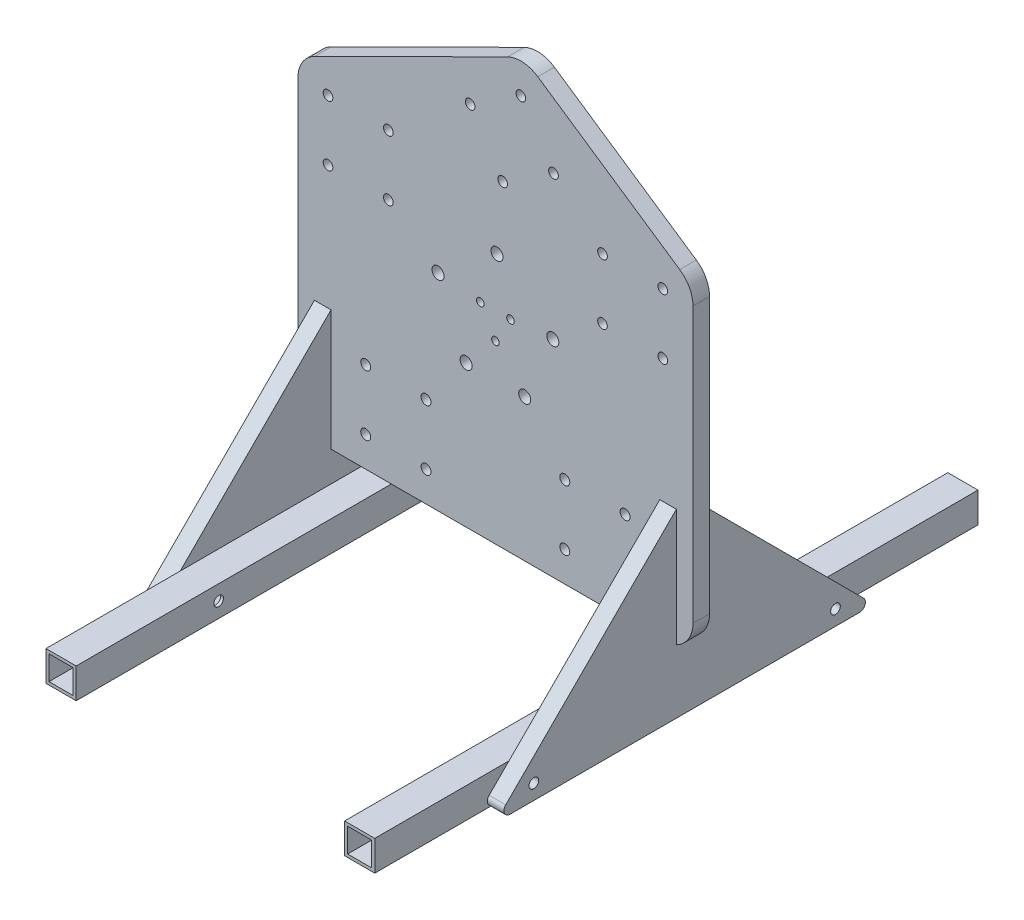
SolidWorks part; units mm, degrees
material "ﾊﾞﾙｻ"
ref_plane "正面" through (0, 0, 0) normal (0, 0, 1) x (1, 0, 0)
ref_plane "平面" through (0, 0, 0) normal (0, 1, 0) x (1, 0, 0)
ref_plane "右側面" through (0, 0, 0) normal (1, 0, 0) x (0, 0, -1)
sketch "ｽｹｯﾁ2" plane through (0, 0, 0) normal (0, 0, 1) x (1, 0, 0)
  line L0 (0, 0) -> (0, -52) construction
  line L5 (-23, -22) -> (-43, -22) construction
  line L6 (-23, -22) -> (-23, -42) construction
  line L7 (-23, -42) -> (-43, -42) construction
  line L8 (-43, -22) -> (-43, -42) construction
  line L9 (43, -22) -> (43, -42) construction
  line L10 (23, -42) -> (43, -42) construction
  line L11 (23, -22) -> (23, -42) construction
  line L12 (23, -22) -> (43, -22) construction
  line L13 (-23, -22) -> (-6, 0) construction
  line L14 (-35.5, 29.0934) -> (-13.5, 12.0934) construction
  line L15 (35.5, 49.0934) -> (35.5, 29.0934) construction
  line L16 (-55.5, 49.0934) -> (-35.5, 49.0934) construction
  line L17 (-55.5, 49.0934) -> (-55.5, 29.0934) construction
  line L18 (-55.5, 29.0934) -> (-35.5, 29.0934) construction
  line L19 (-35.5, 49.0934) -> (-35.5, 29.0934) construction
  line L20 (55.5, 29.0934) -> (35.5, 29.0934) construction
  line L21 (55.5, 49.0934) -> (55.5, 29.0934) construction
  line L22 (55.5, 49.0934) -> (35.5, 49.0934) construction
  line L23 (35.5, 29.0934) -> (13.5, 12.0934) construction
  line L24 (2.4232, 53.2905) -> (0, 25.5934) construction
  line L25 (8.4514, 80.9249) -> (19.2545, 64.0936) construction
  line L26 (8.4514, 80.9249) -> (-8.3799, 70.1218) construction
  line L27 (-8.3799, 70.1218) -> (2.4232, 53.2905) construction
  line L28 (19.2545, 64.0936) -> (2.4232, 53.2905) construction
  line L29 (23, -22) -> (6, 0) construction
  line L30 (-65.5, 49.0934) -> (-65.5, -42)
  line L31 (-55.5, -52) -> (55.5, -52)
  line L32 (65.5, -42) -> (65.5, 49.0934)
  line L33 (61.1036, 57.3759) -> (14.055, 89.2074)
  line L34 (3.9954, 89.8772) -> (-59.956, 58.0457)
  line L35 (0, 12.0934) -> (0, 6.3199) construction
  circle A0 centre (-43, -42) radius 1.65
  circle A1 centre (-43, -22) radius 1.65
  circle A2 centre (-23, -22) radius 1.65
  circle A3 centre (-23, -42) radius 1.65
  circle A8 centre (23, -42) radius 1.65
  circle A9 centre (23, -22) radius 1.65
  circle A10 centre (43, -22) radius 1.65
  circle A11 centre (43, -42) radius 1.65
  circle A12 centre (-55.5, 49.0934) radius 1.6
  circle A13 centre (-55.5, 29.0934) radius 1.6
  circle A14 centre (-35.5, 29.0934) radius 1.6
  circle A15 centre (-35.5, 49.0934) radius 1.6
  circle A16 centre (35.5, 49.0934) radius 1.6
  circle A17 centre (35.5, 29.0934) radius 1.6
  circle A18 centre (55.5, 29.0934) radius 1.6
  circle A19 centre (55.5, 49.0934) radius 1.6
  circle A20 centre (8.4514, 80.9249) radius 1.6
  circle A21 centre (-8.3799, 70.1218) radius 1.6
  circle A22 centre (2.4232, 53.2905) radius 1.6
  circle A23 centre (19.2545, 64.0936) radius 1.6
  circle A24 centre (0, 12.0934) radius 13.5 construction
  arc A25 (-65.5, -42) -> (-55.5, -52) centre (-55.5, -42) ccw
  arc A26 (55.5, -52) -> (65.5, -42) centre (55.5, -42) ccw
  arc A27 (65.5, 49.0934) -> (61.1036, 57.3759) centre (55.5, 49.0934) ccw
  arc A28 (14.055, 89.2074) -> (3.9954, 89.8772) centre (8.4514, 80.9249) ccw
  arc A29 (-65.5, 49.0934) -> (-59.956, 58.0457) centre (-55.5, 49.0934) cw
  circle A30 centre (0, 12.0934) radius 19.5 construction
  circle A31 centre (-19.0266, 16.364) radius 2
  circle A32 centre (0.5243, 31.5863) radius 2
  circle A33 centre (19.0266, 16.364) radius 2
  circle A34 centre (9.7185, -4.8122) radius 2
  circle A35 centre (-9.7185, -4.8122) radius 2
  circle A36 centre (0, 6.3199) radius 1.25
  circle A37 centre (-5, 14.9801) radius 1.25
  circle A38 centre (5, 14.9801) radius 1.25
  point P78 (-6, 16.6629)
  point P79 (0, 12.0934)
  point P83 (0, 12.0934)
  point P84 (0, 0)
  point P85 (0, 0)
  point P86 (-48.6934, -43.9577)
  point P87 (0, 0)
  dimension "D5" = 3.3
  dimension "D9" = 3.2
  dimension "D13" = 27
  dimension "D14" = 10
  dimension "D16" = 6
  dimension "D17" = 4
  dimension "D18" = 2.5
  dimension "D1" = 20
  dimension "D2" = 17
  dimension "D3" = 22
  dimension "D4" = 20
  dimension "D6" = 6
  dimension "D7" = 20
  dimension "D8" = 20
  dimension "D10" = 17
  dimension "D11" = 22
  dimension "D15" = 175
  dimension "D20" = 10
  dimension "D12" = 2
  dimension "D19" = 3
extrude "ﾎﾞｽ - 押し出し1" add sketch "ｽｹｯﾁ2" along normal blind 5.5
sketch "ｽｹｯﾁ4" plane through (0, 0, 0) normal (0, 0, -1) x (-1, 0, 0)
  circle A0 centre (-0.5243, 31.5863) radius 1.7
  circle A1 centre (-19.0266, 16.364) radius 1.7
  circle A2 centre (19.0266, 16.364) radius 1.7
  circle A3 centre (9.7185, -4.8122) radius 1.7
  circle A4 centre (-9.7185, -4.8122) radius 1.7
  circle A6 centre (0, 12.0934) radius 19.5 construction
  circle A7 centre (0, 12.0934) radius 24.5
  circle A8 centre (0, 6.3199) radius 1.6
  circle A9 centre (0, 6.3199) radius 1.25 construction
  circle A10 centre (-5, 14.9801) radius 1.6
  circle A11 centre (5, 14.9801) radius 1.6
  dimension "D1" = 3.4
  dimension "D2" = 5
  dimension "D3" = 3.2
extrude "ﾎﾞｽ - 押し出し2" add sketch "ｽｹｯﾁ4" along normal blind 10 separate body
sketch "ｽｹｯﾁ6" plane through (0, 0, 5.5) normal (0, 0, 1) x (1, 0, 0)
  line L0 (0, 0) -> (0, -52) construction
  line L1 (-55.5, -52) -> (55.5, -52) construction
  line L2 (65.5, -42) -> (65.5, 49.0934) construction
  line L3 (54.5, -32) -> (60, -32)
  line L4 (54.5, -32) -> (54.5, -52)
  line L5 (54.5, -52) -> (60, -52)
  line L6 (60, -32) -> (60, -52)
  line L7 (-54.5, -52) -> (-60, -52)
  line L8 (-60, -32) -> (-60, -52)
  line L9 (-54.5, -32) -> (-60, -32)
  line L10 (-54.5, -32) -> (-54.5, -52)
  point P11 (55.5, -58.7443)
  dimension "D1" = 5.5
  dimension "D2" = 5.5
  dimension "D3" = 20
extrude "ｶｯﾄ - 押し出し1" cut sketch "ｽｹｯﾁ6" against normal through all
sketch "ｽｹｯﾁ7" plane through (60, 0, 0) normal (-1, 0, 0) x (0, 0, 1)
  line L0 (0, -32) -> (5.5, -32)
  line L1 (0, -32) -> (5.5, -32) construction
  line L2 (5.5, -32) -> (5.5, -12)
  line L3 (5.5, -12) -> (65.5, -72)
  line L4 (65.5, -72) -> (-60, -72)
  line L5 (2.75, -72) -> (2.75, -32) construction
  line L6 (5.5, -42) -> (5.5, 49.0934) construction
  line L7 (0, -52) -> (5.5, -52) construction
  line L8 (0, -32) -> (0, -12)
  line L9 (0, -12) -> (-60, -72)
  point P7 (11.6716, -14.7187)
  dimension "D1" = 20
  dimension "D2" = 20
  dimension "D3" = 45
extrude "ﾎﾞｽ - 押し出し3" add sketch "ｽｹｯﾁ7" along normal blind 5.5 separate body
fillet "ﾌｨﾚｯﾄ1" radius 2 2 edges at (57.25, -72, -60) (57.25, -72, 65.5)
mirror "ﾐﾗｰ1" about plane through (0, 0, 0) normal (1, 0, 0) of bodies 104
sketch "ｽｹｯﾁ8" plane through (0, 0, 0) normal (0, 0, 1) x (1, 0, 0)
  line L0 (-53.5, -71) -> (-45.5, -71)
  line L1 (-54.5, -72) -> (-44.5, -72)
  line L2 (-54.5, -72) -> (-54.5, -62)
  line L3 (-54.5, -62) -> (-44.5, -62)
  line L4 (-44.5, -72) -> (-44.5, -62)
  line L5 (-45.5, -71) -> (-45.5, -63)
  line L6 (-53.5, -63) -> (-45.5, -63)
  line L7 (-53.5, -71) -> (-53.5, -63)
  dimension "D1" = 1
  dimension "D2" = 10
  dimension "D3" = 10
extrude "ﾎﾞｽ - 押し出し4" add sketch "ｽｹｯﾁ8" along normal blind 100 and the other way blind 100 separate body
mirror "ﾐﾗｰ2" about plane through (0, 0, 0) normal (1, 0, 0) of bodies 106
sketch "ｽｹｯﾁ9" plane through (60, 0, 0) normal (1, 0, 0) x (0, 0, -1)
  line L0 (-2.75, -50.9303) -> (-2.75, -72) construction
  line L1 (-5.5, -50.9303) -> (0, -50.9303) construction
  line L2 (55.1716, -72) -> (-60.6716, -72) construction
  circle A0 centre (47.25, -67) radius 1.6
  circle A1 centre (-52.75, -67) radius 1.6
  dimension "D1" = 5
  dimension "D3" = 3.2
  dimension "D2" = 100
extrude "ｶｯﾄ - 押し出し2" cut sketch "ｽｹｯﾁ9" against normal through all
